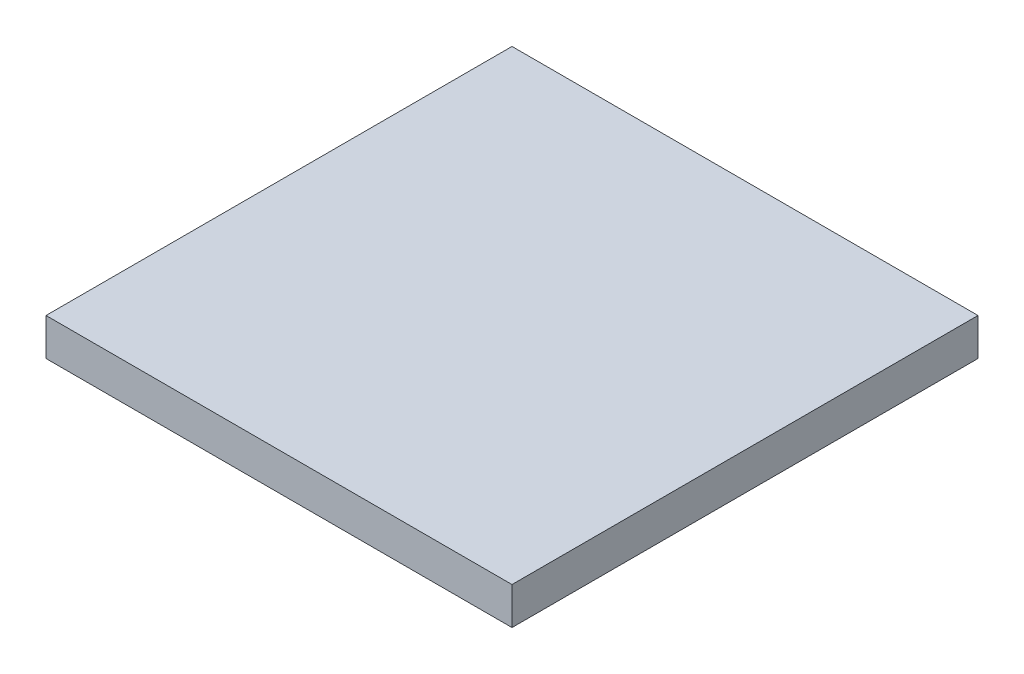
SolidWorks part; units mm, degrees
ref_plane "Front Plane" through (0, 0, 0) normal (0, 0, 1) x (1, 0, 0)
ref_plane "Top Plane" through (0, 0, 0) normal (0, 1, 0) x (1, 0, 0)
ref_plane "Right Plane" through (0, 0, 0) normal (1, 0, 0) x (0, 0, -1)
sketch "Sketch1" plane through (0, 0, 0) normal (0, 1, 0) x (1, 0, 0)
  line L1 (0, 0) -> (25, 0)
  line L2 (0, 0) -> (0, 25)
  line L3 (0, 25) -> (25, 25)
  line L4 (25, 0) -> (25, 25)
  dimension "D1" = 25
extrude "Boss-Extrude1" add sketch "Sketch1" along normal blind 2
